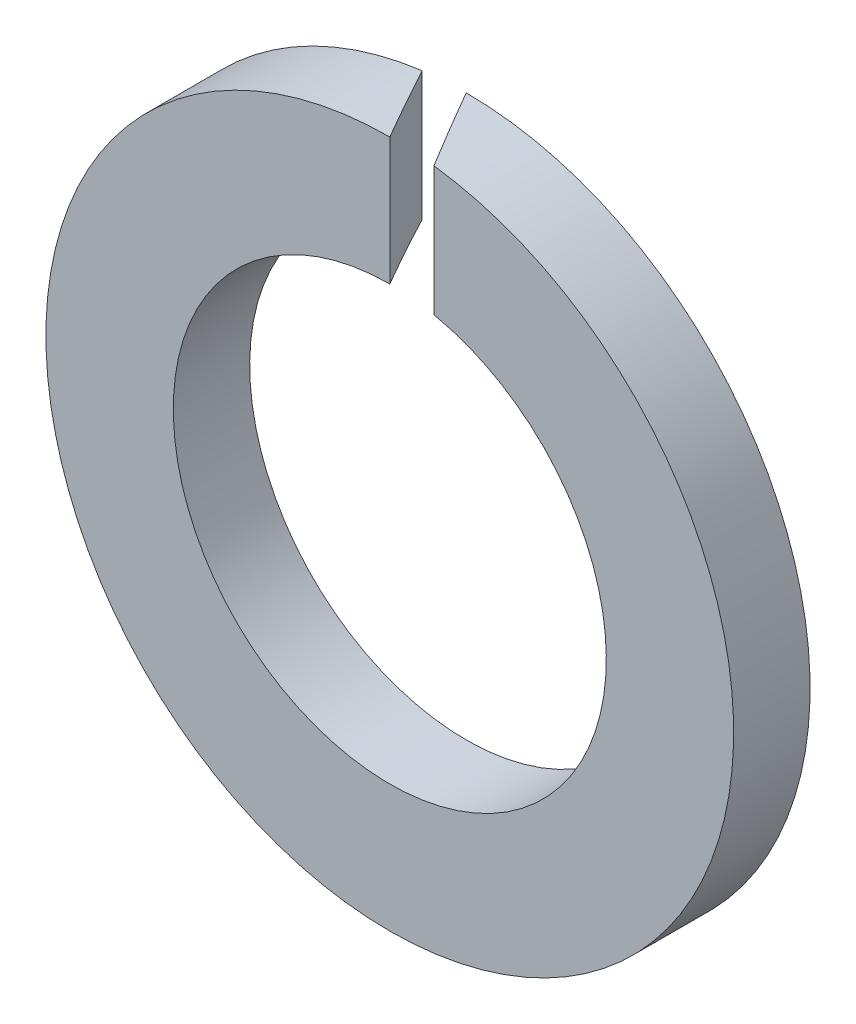
SolidWorks part; units mm, degrees
ref_plane "Front" through (0, 0, 0) normal (0, 0, 1) x (1, 0, 0)
ref_plane "Top" through (0, 0, 0) normal (0, 1, 0) x (1, 0, 0)
ref_plane "Right" through (0, 0, 0) normal (1, 0, 0) x (0, 0, -1)
sketch "Sketch1" plane through (0, 0, 0) normal (0, 0, 1) x (1, 0, 0)
  circle A0 centre (0, 0) radius 1.7
  circle A1 centre (0, 0) radius 2.7
  dimension "d" = 3.4
  dimension "b" = 1
extrude "Base-Extrude" add sketch "Sketch1" against normal blind 0.6
sketch "Sketch2" plane through (0, 0, 0) normal (0, 1, 0) x (1, 0, 0)
  line L0 (0, 0.6) -> (0.3464, 0)
  line L1 (0.3464, 0) -> (0, 0)
  line L3 (0, 0) -> (-0.3464, 0.6)
  line L5 (-0.3464, 0.6) -> (0, 0.6)
  line L7 (2.7, 0.6) -> (-2.7, 0.6) construction
  dimension "m" = 0.3
extrude "Cut-Extrude1" cut sketch "Sketch2" along normal through all
